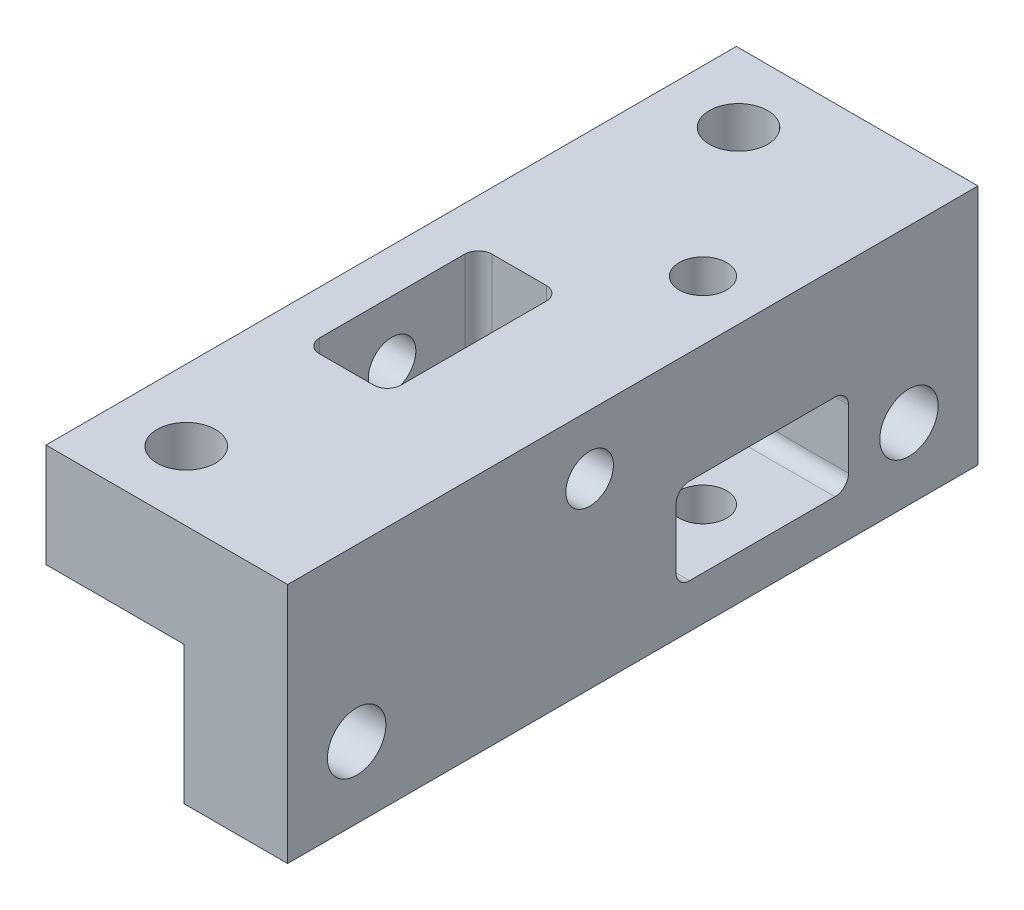
SolidWorks part; units mm, degrees
ref_plane "Front Plane" through (0, 0, 0) normal (1, 0, 0) x (0, 1, 0)
ref_plane "Top Plane" through (0, 0, 0) normal (0, 0, 1) x (0, 1, 0)
ref_plane "Right Plane" through (0, 0, 0) normal (0, 1, 0) x (-1, 0, 0)
sketch "Sketch2" plane through (0, 0, 0) normal (0, 0, 1) x (0, 1, 0)
  line L0 (0, 0) -> (-17.78, 0)
  line L1 (-17.78, 0) -> (-17.78, 7.62)
  line L2 (-17.78, 7.62) -> (-7.62, 7.62)
  line L3 (-7.62, 7.62) -> (-7.62, 17.78)
  line L4 (-7.62, 17.78) -> (0, 17.78)
  line L5 (0, 17.78) -> (0, 0)
  line L7 (-60.1663, 60.1662) -> (3.3337, 60.1662) construction
  line L8 (-60.1663, 60.1662) -> (-60.1663, -3.3338) construction
  line L9 (-60.1663, -3.3338) -> (3.3338, -3.3338) construction
  line L10 (3.3337, 60.1662) -> (3.3338, -3.3338) construction
  line L11 (-56.8325, 56.8325) -> (0, 56.8325) construction
  line L12 (-56.8325, 56.8325) -> (-56.8325, 0) construction
  line L13 (-56.8325, 0) -> (0, 0) construction
  line L14 (0, 56.8325) -> (0, 0) construction
  line L15 (-47.4663, 47.4662) -> (-9.3662, 47.4662) construction
  line L16 (-47.4663, 47.4662) -> (-47.4663, 9.3662) construction
  line L17 (-47.4663, 9.3662) -> (-9.3662, 9.3662) construction
  line L18 (-9.3662, 47.4662) -> (-9.3662, 9.3662) construction
  line L19 (-13.3662, 9.3662) -> (-9.3662, 9.3662) construction
  line L20 (-13.3662, 9.3662) -> (-13.3662, -0.6338) construction
  line L21 (-13.3662, -0.6338) -> (-9.3662, -0.6338) construction
  line L22 (-9.3662, 9.3662) -> (-9.3662, -0.6338) construction
  point P15 (-28.4163, 60.1662)
  point P16 (-28.4163, 56.8325)
  point P17 (-56.8325, 28.4162)
  point P18 (-60.1663, 28.4162)
  point P19 (-28.4163, 47.4662)
  point P24 (-47.4662, 28.4162)
  point P25 (-11.3662, -0.6338)
  point P31 (-9.3662, 4.3662)
  dimension "D1" = 17.78
  dimension "D2" = 17.78
  dimension "D3" = 63.5
  dimension "D4" = 56.8325
  dimension "D5" = 38.1
  dimension "D6" = 38.1
  dimension "D7" = 4
  dimension "D8" = 10
  dimension "D9" = 16.7
  dimension "D10" = 7.62
extrude "Boss-Extrude2" add sketch "Sketch2" along normal blind 50.8
sketch "Sketch3" plane through (0, 0, 0) normal (0, 1, 0) x (-1, 0, 0)
  line L0 (9.3662, 0) -> (-0.6338, 0) construction
  line L1 (9.3662, 0) -> (-0.6338, 0) construction
  circle A0 centre (4.3662, 15.875) radius 1.75
  point P4 (4.3662, 0)
  dimension "D1" = 3.5
  dimension "D2" = 15.875
extrude "Cut-Extrude1" cut sketch "Sketch3" against normal blind 76.2
sketch "Sketch4" plane through (-7.62, 0, 0) normal (-1, 0, 0) x (0, -1, 0)
  line L1 (8.1912, 22.225) -> (14.5412, 22.225)
  line L2 (8.1912, 22.225) -> (8.1912, 9.525)
  line L3 (8.1912, 9.525) -> (14.5412, 9.525)
  line L4 (14.5412, 22.225) -> (14.5412, 9.525)
  line L5 (17.78, 14.125) -> (17.78, 17.625) construction
  line L6 (17.78, 14.125) -> (17.78, 17.625) construction
  line L8 (7.62, 0) -> (17.78, 0) construction
  line L9 (13.3662, 0) -> (9.3662, 0) construction
  line L10 (13.3662, 0) -> (9.3662, 0) construction
  line L11 (7.62, 50.8) -> (17.78, 50.8) construction
  circle A0 centre (12.5412, 5.08) radius 2.15
  circle A1 centre (12.5412, 5.08) radius 3.75 construction
  circle A2 centre (12.5412, 45.72) radius 2.15
  point P6 (14.5412, 15.875)
  point P9 (17.78, 15.875)
  point P10 (12.5412, 8.83)
  point P14 (12.5412, 7.23)
  point P15 (11.3662, 0)
  point P18 (-3.3338, 0)
  point P24 (11.3662, 9.525)
  dimension "D3" = 4.3
  dimension "D1" = 6.35
  dimension "D2" = 12.7
  dimension "D4" = 1.6
  dimension "D5" = 15.875
  dimension "D6" = 5.08
  dimension "D7" = 5.08
extrude "Cut-Extrude2" cut sketch "Sketch4" against normal blind 76.2
sketch "Sketch6" plane through (-17.78, 0, 0) normal (-1, 0, 0) x (0, -1, 0)
  line L0 (0, 50.8) -> (0, 0) construction
  line L1 (0, 0) -> (7.62, 0) construction
  circle A0 centre (4.3663, 28.575) radius 1.75
  dimension "D2" = 3.5
  dimension "D1" = 4.3663
  dimension "D3" = 28.575
extrude "Cut-Extrude3" cut sketch "Sketch6" against normal blind 76.2
sketch "Sketch7" plane through (0, -7.62, 0) normal (0, -1, 0) x (1, 0, 0)
  line L0 (-17.78, 50.8) -> (-17.78, 0) construction
  line L1 (-14.5412, 34.925) -> (-8.5412, 34.925)
  line L2 (-14.5412, 34.925) -> (-14.5412, 22.225)
  line L3 (-14.5412, 22.225) -> (-8.5412, 22.225)
  line L4 (-8.5412, 34.925) -> (-8.5412, 22.225)
  line L5 (-17.78, 30.325) -> (-17.78, 26.825) construction
  line L6 (-17.78, 30.325) -> (-17.78, 26.825) construction
  line L7 (-7.62, 47.87) -> (-7.62, 43.57) construction
  line L8 (-7.62, 7.23) -> (-7.62, 2.93) construction
  line L9 (-7.62, 47.87) -> (-7.62, 43.57) construction
  line L10 (-7.62, 7.23) -> (-7.62, 2.93) construction
  circle A0 centre (-12.5412, 45.72) radius 2.15
  circle A1 centre (-12.5412, 5.08) radius 2.15
  point P8 (-17.78, 28.575)
  point P9 (-14.5412, 28.575)
  point P18 (-7.62, 5.08)
  point P21 (-7.62, 45.72)
  dimension "D5" = 4.3
  dimension "D1" = 6
  dimension "D2" = 3.2388
  dimension "D3" = 12.7
  dimension "D4" = 15.875
extrude "Cut-Extrude4" cut sketch "Sketch7" against normal blind 76.2
fillet "Fillet1" radius 1 8 edges at (-3.81, -14.5412, 9.525) (-3.81, -14.5412, 22.225) (-3.81, -8.1912, 22.225) (-3.81, -8.1912, 9.525) (-8.5412, -3.81, 22.225) (-14.5412, -3.81, 22.225) (-8.5412, -3.81, 34.925) (-14.5412, -3.81, 34.925)
